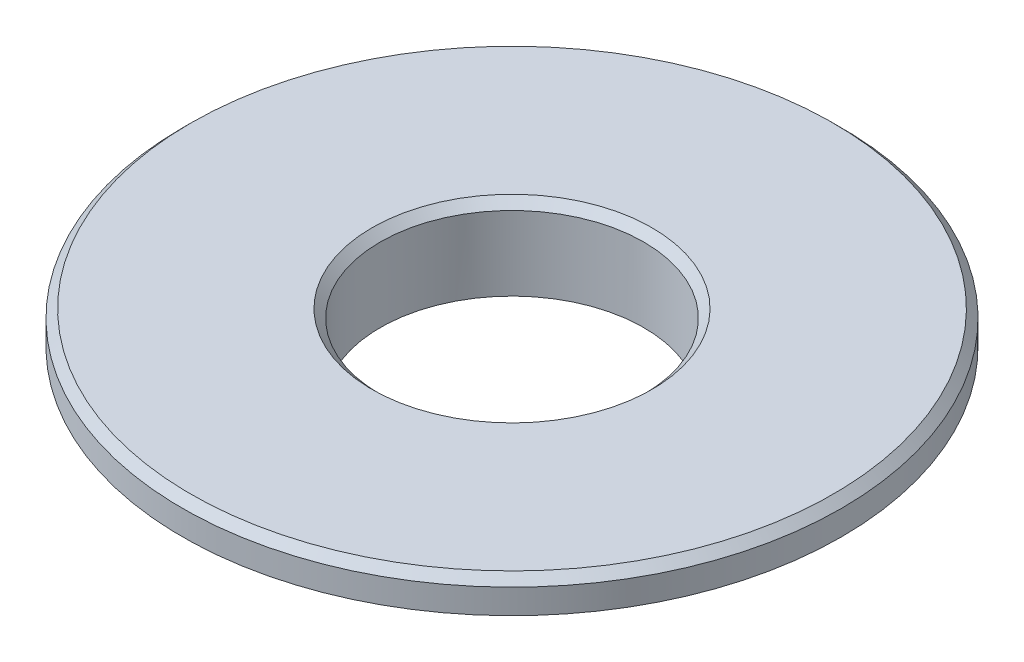
SolidWorks part; units mm, degrees
material "Lega 1060"
ref_plane "Piano frontale" through (0, 0, 0) normal (0, 0, 1) x (1, 0, 0)
ref_plane "Piano superiore" through (0, 0, 0) normal (0, 1, 0) x (1, 0, 0)
ref_plane "Piano destro" through (0, 0, 0) normal (1, 0, 0) x (0, 0, -1)
sketch "Schizzo1" plane through (0, 0, 0) normal (0, 0, 1) x (1, 0, 0)
  line L0 (0, -42.9737) -> (0, 42.9737) construction
  line L1 (8, 0) -> (20, 0)
  line L2 (20, 0) -> (20, -2)
  line L3 (20, -2) -> (9.5, -2)
  line L4 (9.5, -2) -> (9.5, -5)
  line L5 (9.5, -5) -> (8, -5)
  line L6 (8, -5) -> (8, 0)
  point P3 (0, 0)
  dimension "D1" = 20
  dimension "D2" = 1.5
  dimension "D3" = 8
  dimension "D4" = 3
  dimension "D5" = 2
revolve "Rivoluzione1" add sketch "Schizzo1" angle 360 about L0
chamfer "Smusso1" distance 0.5 angle 45 3 edges at (9.5, -5, 0) (8, 0, 0) (20, 0, 0)
